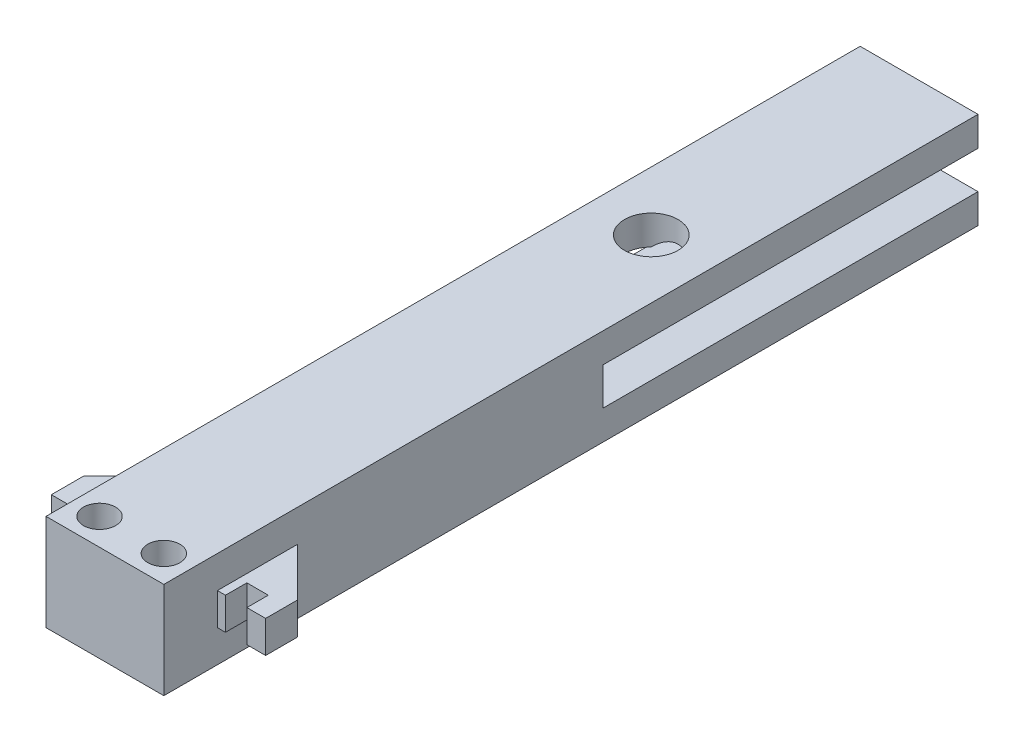
SolidWorks part; units mm, degrees
ref_plane "Front Plane" through (0, 0, 0) normal (0, 0, 1) x (1, 0, 0)
ref_plane "Top Plane" through (0, 0, 0) normal (0, 1, 0) x (1, 0, 0)
ref_plane "Right Plane" through (0, 0, 0) normal (1, 0, 0) x (0, 0, -1)
sketch "Sketch1" plane through (0, 0, 0) normal (0, 1, 0) x (1, 0, 0)
  line L1 (-5.5, 38) -> (5.5, 38)
  line L2 (-5.5, 38) -> (-5.5, -38)
  line L3 (-5.5, -38) -> (5.5, -38)
  line L4 (5.5, 38) -> (5.5, -38)
  line L5 (-5.5, 38) -> (5.5, -38) construction
  line L6 (-5.5, -38) -> (5.5, 38) construction
  point P0 (0, 0)
  dimension "D1" = 76
  dimension "D2" = 11
extrude "Boss-Extrude1" add sketch "Sketch1" along normal blind 9
ref_plane "Plane1" through (0, 0, 0) normal (-1, 0, 0) x (0, 0, 1)
sketch "Sketch3" plane through (0, 0, 0) normal (-1, 0, 0) x (0, 0, 1)
  line L0 (-38, 4.5) -> (27, 4.5)
  line L2 (38, 9) -> (38, 0) construction
  line L3 (-38, 9) -> (-38, 0) construction
  line L4 (31, 0.5) -> (31, 0)
  line L5 (-38, 0) -> (38, 0) construction
  arc A1 (31, 0.5) -> (27, 4.5) centre (27, 0.5) ccw
  point P9 (31, 4.5)
  point P14 (-38, 4.5)
  dimension "D1" = 4
  dimension "D2" = 7
sketch "Sketch4" plane through (0, 0, -38) normal (0, 0, -1) x (-1, 0, 0)
  line L0 (-5.5, 9) -> (-5.5, 0) construction
  line L1 (0, -55.5125) -> (0, 55.5125) construction
  circle A0 centre (0, 4.5) radius 2.5
  point P8 (-5.5, 4.5)
  dimension "D1" = 5
sweep "Cut-Sweep2" cut profiles "Sketch4" path "Sketch3"
sketch "Sketch5" plane through (-5.5, 0, 0) normal (-1, 0, 0) x (0, 0, 1)
  line L0 (38, 9) -> (38, 0) construction
  line L1 (30, 6) -> (33, 6)
  line L2 (30, 6) -> (30, 3)
  line L3 (30, 3) -> (33, 3)
  line L4 (33, 6) -> (33, 3)
  line L5 (30, 6) -> (33, 3) construction
  line L6 (30, 3) -> (33, 6) construction
  point P0 (31.5, 4.5)
  point P7 (38, 4.5)
  point P8 (33, 4.5)
  dimension "D1" = 3
  dimension "D2" = 5
extrude "Boss-Extrude2" add sketch "Sketch5" along normal blind 4.5
ref_plane "Plane2" through (0, 0, 0) normal (-1, 0, 0) x (0, 0, 1)
mirror "Mirror1" about plane through (0, 0, 0) normal (-1, 0, 0) of "Boss-Extrude2"
sketch "Sketch6" plane through (0, 0, 33) normal (0, 0, 1) x (1, 0, 0)
  line L1 (-8.25, 6) -> (-6.25, 6)
  line L2 (-8.25, 6) -> (-8.25, 3)
  line L3 (-8.25, 3) -> (-6.25, 3)
  line L4 (-6.25, 6) -> (-6.25, 3)
  line L5 (-8.25, 6) -> (-6.25, 3) construction
  line L6 (-8.25, 3) -> (-6.25, 6) construction
  line L7 (-10, 3) -> (-5.5, 3) construction
  line L8 (-5.5, 3) -> (-5.5, 6) construction
  point P0 (-7.25, 4.5)
  dimension "D1" = 0.75
  dimension "D2" = 2
extrude "Cut-Extrude2" cut sketch "Sketch6" against normal offset from surface (2 mm away) 1 up to face at (-7.75, 4.5, 30)
mirror "Mirror2" about plane through (0, 0, 0) normal (-1, 0, 0) of "Cut-Extrude2"
sketch "Sketch7" plane through (0, 6, 0) normal (0, 1, 0) x (1, 0, 0)
  line L0 (-10, -30) -> (-5.5, -25.5)
  line L1 (-5.5, 38) -> (-5.5, -38) construction
  line L2 (-5.5, -25.5) -> (-5.5, -30)
  line L3 (-5.5, -30) -> (-10, -30)
extrude "Boss-Extrude3" add sketch "Sketch7" against normal up to surface (3 mm away) up to face at (-7.5, 3, 31.75)
mirror "Mirror3" about plane through (0, 0, 0) normal (-1, 0, 0) of "Boss-Extrude3"
sketch "Sketch8" plane through (0, 0, 0) normal (0, -1, 0) x (1, 0, 0)
  line L5 (-5.5, 38) -> (5.5, 38) construction
  line L16 (0, 38) -> (0, 0) construction
  line L19 (-5.5, -38) -> (-5.5, 38) construction
  circle A0 centre (-3, 35.5) radius 1.5
  circle A1 centre (3, 35.5) radius 1.5
  point P9 (0, 0)
  point P11 (0.7158, 39.1708)
  dimension "D1" = 3
  dimension "D2" = 2.5
  dimension "D3" = 2.5
sketch "Sketch10" plane through (0, 0, -38) normal (0, 0, -1) x (-1, 0, 0)
  line L0 (10, 6.25) -> (1.7146, 6.25) construction
  line L1 (-5.5, 6.25) -> (5.5, 6.25)
  line L2 (-5.5, 6.25) -> (-5.5, 2.75)
  line L3 (-5.5, 2.75) -> (5.5, 2.75)
  line L4 (5.5, 6.25) -> (5.5, 2.75)
  line L5 (-5.5, 6.25) -> (5.5, 2.75) construction
  line L6 (-5.5, 2.75) -> (5.5, 6.25) construction
  point P0 (0, 4.5)
  dimension "D2" = 11
extrude "Cut-Extrude5" cut sketch "Sketch10" against normal blind 35
sketch "Sketch11" plane through (0, 9, 0) normal (0, 1, 0) x (1, 0, 0)
  line L0 (5.5, 38) -> (-5.5, 38) construction
  circle A0 centre (0, 13) radius 2.5
  dimension "D1" = 5
  dimension "D2" = 25
extrude "Cut-Extrude6" cut sketch "Sketch11" against normal up to next
extrude "Cut-Extrude8" cut sketch "Sketch8" against normal up to next
